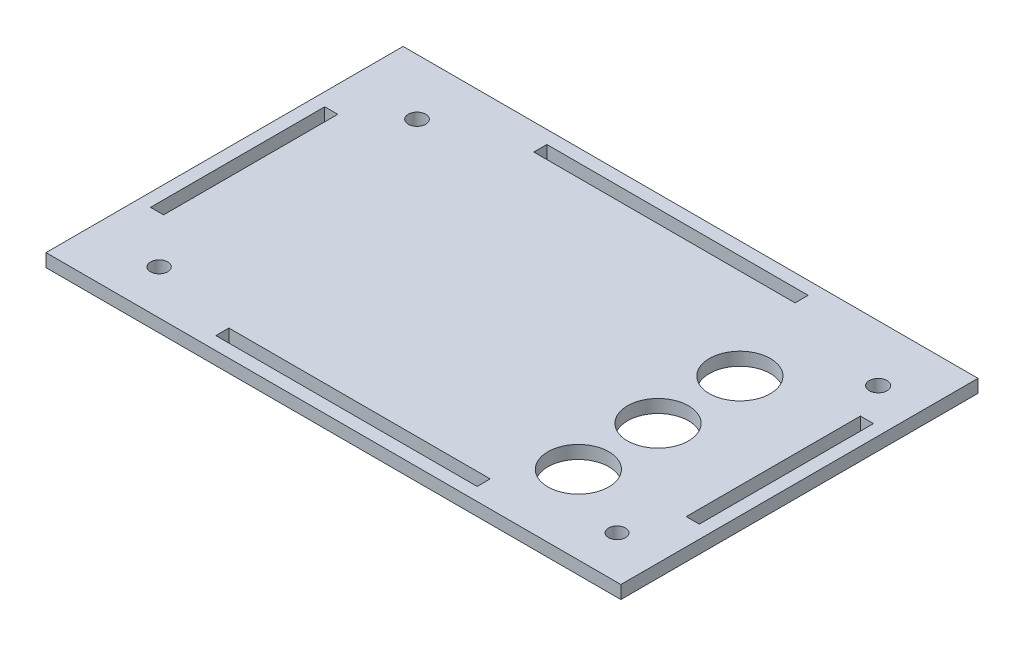
SolidWorks part; units mm, degrees
ref_plane "Front Plane" through (0, 0, 0) normal (0, 0, 1) x (1, 0, 0)
ref_plane "Top Plane" through (0, 0, 0) normal (0, 1, 0) x (1, 0, 0)
ref_plane "Right Plane" through (0, 0, 0) normal (1, 0, 0) x (0, 0, -1)
sketch "Sketch2" plane through (0, 0, 0) normal (0, 1, 0) x (1, 0, 0)
  line L0 (0, 70) -> (0, 0) construction
  line L1 (0, 0) -> (-120, 0) construction
  line L2 (0, 0) -> (0, 70) construction
  line L3 (0, 70) -> (-120, 70) construction
  line L4 (-120, 0) -> (-120, 70) construction
  line L9 (0, 35) -> (1.5, 35) construction
  line L10 (-120, 70) -> (-120, 0) construction
  line L11 (3, 55) -> (0, 55)
  line L12 (3, 55) -> (3, 15)
  line L13 (3, 15) -> (0, 15)
  line L14 (0, 55) -> (0, 15)
  line L15 (3, 55) -> (0, 15) construction
  line L16 (3, 15) -> (0, 55) construction
  line L17 (-120, 35) -> (-121.5, 35) construction
  line L18 (-60, 70) -> (-60, 71.5) construction
  line L19 (-123, 55) -> (-120, 55)
  line L20 (-123, 55) -> (-123, 15)
  line L21 (-123, 15) -> (-120, 15)
  line L22 (-120, 55) -> (-120, 15)
  line L23 (-123, 55) -> (-120, 15) construction
  line L24 (-123, 15) -> (-120, 55) construction
  line L25 (-60, 0) -> (-60, -1.5) construction
  line L26 (-30, 73) -> (-90, 73)
  line L27 (-30, 73) -> (-30, 70)
  line L28 (-30, 70) -> (-90, 70)
  line L29 (-90, 73) -> (-90, 70)
  line L30 (-30, 73) -> (-90, 70) construction
  line L31 (-30, 70) -> (-90, 73) construction
  line L32 (0, 0) -> (6, 0) construction
  line L33 (-30, -3) -> (-90, -3)
  line L34 (-30, -3) -> (-30, 0)
  line L35 (-30, 0) -> (-90, 0)
  line L36 (-90, -3) -> (-90, 0)
  line L37 (-30, -3) -> (-90, 0) construction
  line L38 (-30, 0) -> (-90, -3) construction
  line L39 (6, 0) -> (6, -6) construction
  line L40 (-120, 70) -> (-120, 76) construction
  line L41 (-120, 76) -> (-126, 76) construction
  line L43 (6, -6) -> (-126, -6)
  line L44 (6, -6) -> (6, 76)
  line L45 (6, 76) -> (-126, 76)
  line L46 (-126, -6) -> (-126, 76)
  circle A0 centre (-109.9268, 63.1138) radius 2.0066
  circle A1 centre (-110.1808, 4.1548) radius 1.9733
  circle A2 centre (-4.0043, 63.0805) radius 2.0377
  circle A3 centre (-4.7202, 3.8378) radius 1.9401
  circle A4 centre (-21.7888, 49.1111) radius 7
  circle A5 centre (-21.7888, 30.3158) radius 7
  circle A6 centre (-21.7888, 12.0285) radius 7
extrude "Boss-Extrude1" add sketch "Sketch2" along normal blind 3
